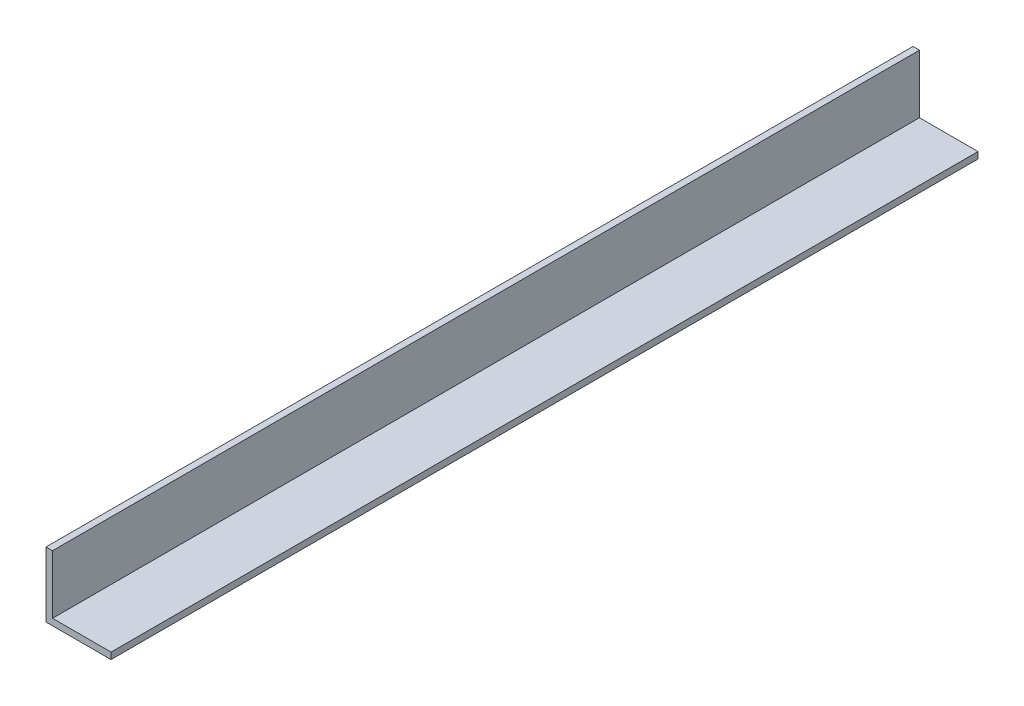
SolidWorks part; units mm, degrees
material "Ferro duttile"
ref_plane "Piano frontale" through (0, 0, 0) normal (0, 0, 1) x (1, 0, 0)
ref_plane "Piano superiore" through (0, 0, 0) normal (0, 1, 0) x (1, 0, 0)
ref_plane "Piano destro" through (0, 0, 0) normal (1, 0, 0) x (0, 0, -1)
sketch "Schizzo1" plane through (0, 0, 0) normal (0, 0, 1) x (1, 0, 0)
  line L0 (0, 30) -> (0, 0)
  line L1 (0, 0) -> (30, 0)
  line L2 (30, 0) -> (30, 3)
  line L3 (30, 3) -> (3, 3)
  line L4 (3, 3) -> (3, 30)
  line L5 (3, 30) -> (0, 30)
  dimension "D1" = 3
  dimension "D2" = 3
  dimension "D3" = 30
  dimension "D4" = 30
extrude "Estrusione-Estrusione1" add sketch "Schizzo1" along normal blind 400
